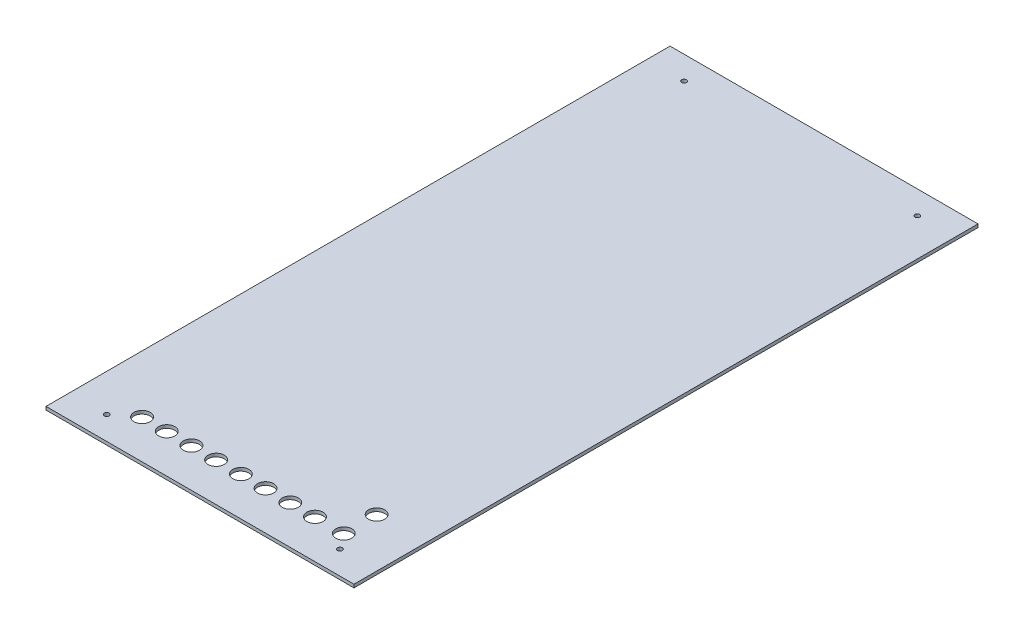
SolidWorks part; units mm, degrees
ref_plane "Front Plane" through (0, 0, 0) normal (0, 0, 1) x (1, 0, 0)
ref_plane "Top Plane" through (0, 0, 0) normal (0, 1, 0) x (1, 0, 0)
ref_plane "Right Plane" through (0, 0, 0) normal (1, 0, 0) x (0, 0, -1)
sketch "Sketch1" plane through (0, 0, 0) normal (0, 1, 0) x (1, 0, 0)
  line L0 (-74.93, -168.55) -> (74.93, -168.55) construction
  line L1 (-74.93, 181.61) -> (74.93, 181.61)
  line L2 (-74.93, 181.61) -> (-74.93, -181.61)
  line L3 (-74.93, -181.61) -> (74.93, -181.61)
  line L4 (74.93, 181.61) -> (74.93, -181.61)
  line L5 (-74.93, 181.61) -> (74.93, -181.61) construction
  line L6 (-74.93, -181.61) -> (74.93, 181.61) construction
  line L7 (-95, 192.5) -> (95, 192.5)
  line L8 (-95, 192.5) -> (-95, -192.5)
  line L9 (-95, -192.5) -> (95, -192.5)
  line L10 (95, 192.5) -> (95, -192.5)
  line L11 (-95, 192.5) -> (95, -192.5) construction
  line L12 (-95, -192.5) -> (95, 192.5) construction
  line L13 (64.77, -168.55) -> (64.77, -148.27) construction
  line L14 (0, 192.5) -> (0, -192.5) construction
  line L15 (-95, 0) -> (95, 0) construction
  circle A0 centre (-59.69, -168.55) radius 5
  circle A1 centre (-44.45, -168.55) radius 5
  circle A2 centre (-29.21, -168.55) radius 5
  circle A3 centre (-13.97, -168.55) radius 5
  circle A4 centre (1.27, -168.55) radius 5
  circle A5 centre (16.51, -168.55) radius 5
  circle A6 centre (31.75, -168.55) radius 5
  circle A7 centre (46.99, -168.55) radius 5
  circle A8 centre (64.77, -168.55) radius 5
  circle A9 centre (64.77, -148.27) radius 5
  circle A10 centre (-71.93, 178.11) radius 1.5
  circle A11 centre (71.93, 178.11) radius 1.5
  circle A12 centre (71.93, -178.11) radius 1.5
  circle A13 centre (-71.93, -178.11) radius 1.5
  point P0 (0, 0)
  point P5 (0, 0)
  dimension "D5" = 13.06
  dimension "D6" = 15.24
  dimension "D7" = 10
  dimension "D9" = 10
  dimension "D10" = 17.78
  dimension "D12" = 10
  dimension "D13" = 3
  dimension "D14" = 3
  dimension "D15" = 3.5
  dimension "D1" = 149.86
  dimension "D2" = 363.22
  dimension "D3" = 10.89
  dimension "D4" = 20.07
  dimension "D11" = 20.28
  dimension "D8" = 8
extrude "Boss-Extrude1" add sketch "Sketch1" along normal blind 2 contours L10 L7 L8 L9 L1 L4 L3 L2 | L4 L1 L2 L3 A9 A8 A7 A6 A5 A4 A3 A2 A1 A0
sketch "Sketch3" plane through (0, 2, 0) normal (0, 1, 0) x (1, 0, 0)
  line L0 (-95, -192.5) -> (95, -192.5) construction
  line L1 (-95, 192.5) -> (-95, -192.5) construction
  line L2 (-71.93, -178.11) -> (71.93, -178.11) construction
  line L3 (-59.69, -168.55) -> (-59.69, -178.11) construction
  line L4 (64.77, -168.55) -> (64.77, -178.11) construction
  line L5 (64.77, -148.27) -> (64.77, -168.55) construction
  line L6 (-59.69, -168.55) -> (-44.45, -168.55) construction
  circle A0 centre (-13.97, -168.55) radius 5 construction
  circle A1 centre (71.93, 178.11) radius 1.5
  circle A2 centre (-71.93, 178.11) radius 1.5
  circle A3 centre (-71.93, -178.11) radius 1.5
  circle A4 centre (71.93, -178.11) radius 1.5
  circle A5 centre (1.27, -168.55) radius 5 construction
  circle A6 centre (-44.45, -168.55) radius 5 construction
  circle A7 centre (-29.21, -168.55) radius 5 construction
  circle A8 centre (16.51, -168.55) radius 5 construction
  circle A9 centre (31.75, -168.55) radius 5 construction
  circle A10 centre (46.99, -168.55) radius 5 construction
  circle A11 centre (64.77, -168.55) radius 5 construction
  dimension "D1" = 356.22
  dimension "D2" = 14.39
  dimension "D3" = 143.86
  dimension "D6" = 15.24
  dimension "D9" = 27.48
  dimension "D10" = 42.72
  dimension "D11" = 57.96
  dimension "D12" = 73.2
  dimension "D13" = 88.44
  dimension "D14" = 103.68
  dimension "D15" = 118.92
  dimension "D16" = 136.7
  dimension "D4" = 23.07
  dimension "D5" = 12.24
  dimension "D7" = 9.56
  dimension "D8" = 29.84
